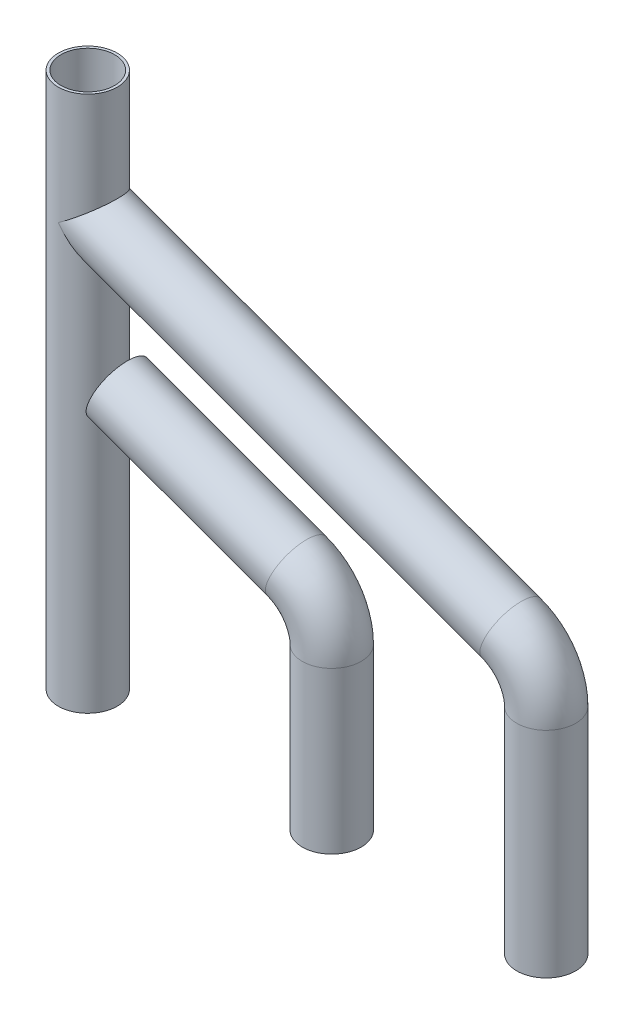
SolidWorks part; units mm, degrees
ref_plane "Front Plane" through (0, 0, 0) normal (0, 0, 1) x (1, 0, 0)
ref_plane "Top Plane" through (0, 0, 0) normal (0, 1, 0) x (1, 0, 0)
ref_plane "Right Plane" through (0, 0, 0) normal (1, 0, 0) x (0, 0, -1)
sketch "Sketch1" plane through (0, 0, 0) normal (0, 1, 0) x (1, 0, 0)
  circle A0 centre (0, 0) radius 6.35
  circle A1 centre (0, 0) radius 6.985
  dimension "D1" = 12.7
  dimension "D2" = 13.97
extrude "Boss-Extrude1" add sketch "Sketch1" along normal blind 127
sketch "Sketch2" plane through (0, 0, 0) normal (0, 0, 1) x (1, 0, 0)
  line L0 (6.985, 96.672) -> (100.2287, 62.7341)
  line L1 (6.985, 0) -> (6.985, 127) construction
  line L2 (108.585, 50.8) -> (108.585, 0)
  line L5 (-6.985, 0) -> (6.985, 0) construction
  arc A0 (100.2287, 62.7341) -> (108.585, 50.8) centre (95.885, 50.8) cw
  dimension "D10" = 12.7
  dimension "D2" = 50.8
  dimension "D3" = 110
  dimension "D4" = 0
  dimension "D5" = 101.6
ref_plane "Plane1" through (108.585, 0, 0) normal (0, -1, 0) x (-1, 0, 0)
sketch "Sketch3" plane through (108.585, 0, 0) normal (0, -1, 0) x (-1, 0, 0)
  line L0 (0, 0) -> (8.3563, 0) construction
  circle A0 centre (0, 0) radius 6.35
  circle A1 centre (0, 0) radius 6.985
  point P5 (0, 0)
  point P6 (0, 0)
  dimension "D1" = 12.7
  dimension "D2" = 13.97
sweep "Sweep10" add profiles "Sketch3" path "Sketch2"
sketch "Sketch6" plane through (68.3418, -24.8744, 0) normal (-0.9397, 0.342, 0) x (0, 0, 1)
  circle A1 centre (0, 93.231) radius 6.985
  circle A2 centre (0, 93.231) radius 6.985
  dimension "D1" = 0
extrude "Boss-Extrude3" add sketch "Sketch6" along normal up to surface (96.6855 mm away)
sketch "Sketch8" plane through (0, 0, 0) normal (0, 0, 1) x (1, 0, 0)
  line L0 (6.985, 65.4823) -> (49.4287, 50.0341)
  line L1 (6.985, 0) -> (6.985, 89.2387) construction
  line L2 (57.785, 38.1) -> (57.785, 0)
  arc A0 (49.4287, 50.0341) -> (57.785, 38.1) centre (45.085, 38.1) cw
  point P1 (0, 0)
  point P4 (0, 0)
  point P6 (0, 0)
  point P10 (0, 0)
  dimension "D2" = 12.7
  dimension "D1" = 50.8
  dimension "D3" = 110
  dimension "D4" = 38.1
ref_plane "Plane3" through (57.785, 0, 0) normal (0, -1, 0) x (-1, 0, 0)
sketch "Sketch9" plane through (57.785, 0, 0) normal (0, -1, 0) x (-1, 0, 0)
  circle A0 centre (0, 0) radius 6.35
  circle A1 centre (0, 0) radius 6.985
  dimension "D1" = 12.7
  dimension "D2" = 13.97
sweep "Sweep14" add profiles "Sketch9" path "Sketch8"
